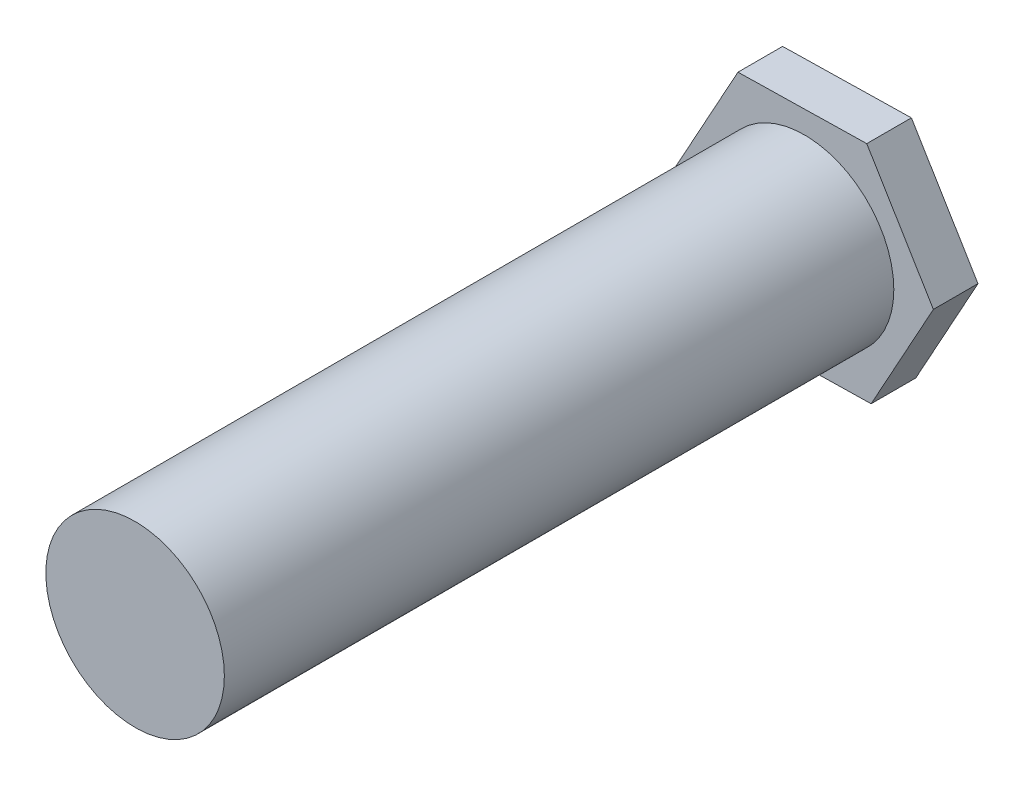
SolidWorks part; units mm, degrees
ref_plane "Front Plane" through (0, 0, 0) normal (0, 0, 1) x (1, 0, 0)
ref_plane "Top Plane" through (0, 0, 0) normal (0, 1, 0) x (1, 0, 0)
ref_plane "Right Plane" through (0, 0, 0) normal (1, 0, 0) x (0, 0, -1)
sketch "Sketch1" plane through (0, 0, 0) normal (0, 0, 1) x (1, 0, 0)
  line L1 (17.7039, 32.1038) -> (-18.9508, 31.3839)
  line L2 (-18.9508, 31.3839) -> (-36.6547, -0.7199)
  line L3 (-36.6547, -0.7199) -> (-17.7039, -32.1038)
  line L4 (-17.7039, -32.1038) -> (18.9508, -31.3839)
  line L5 (18.9508, -31.3839) -> (36.6547, 0.7199)
  line L6 (36.6547, 0.7199) -> (17.7039, 32.1038)
  circle A0 centre (0, 0) radius 31.75 construction
  dimension "D1" = 63.5
extrude "Boss-Extrude1" add sketch "Sketch1" along normal blind 12.7
sketch "Sketch2" plane through (0, 0, 12.7) normal (0, 0, 1) x (1, 0, 0)
  circle A0 centre (0, 0) radius 25.4
  dimension "D1" = 50.8
extrude "Boss-Extrude2" add sketch "Sketch2" along normal blind 190.5
